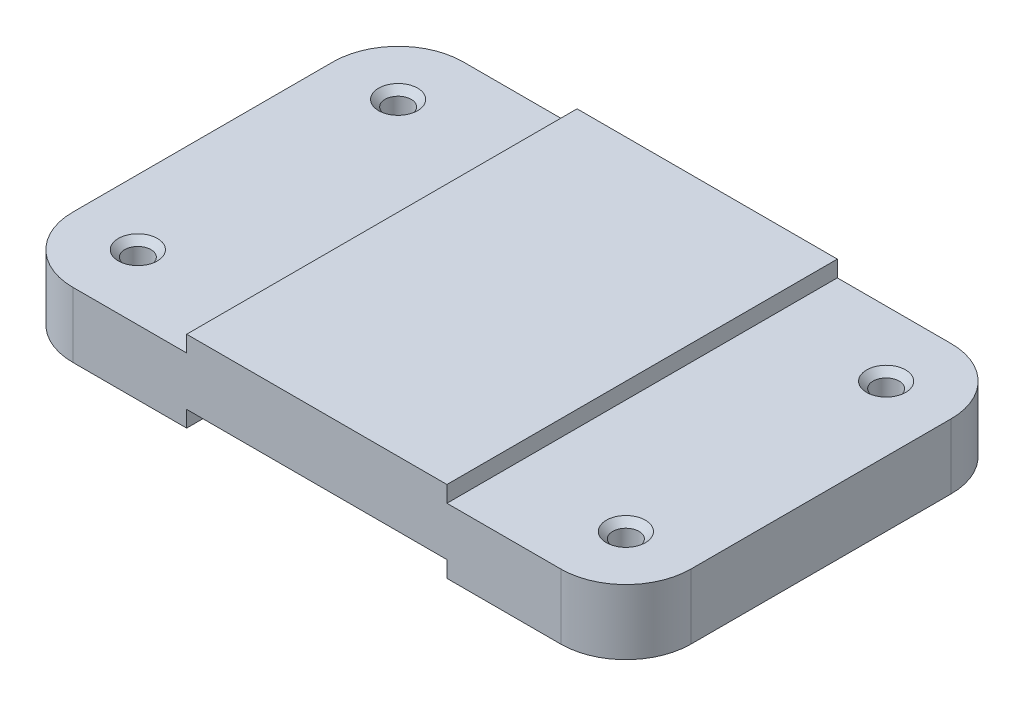
SolidWorks part; units mm, degrees
ref_plane "Front Plane" through (0, 0, 0) normal (0, 0, 1) x (1, 0, 0)
ref_plane "Top Plane" through (0, 0, 0) normal (0, 1, 0) x (1, 0, 0)
ref_plane "Right Plane" through (0, 0, 0) normal (1, 0, 0) x (0, 0, -1)
sketch "Sketch1" plane through (0, 0, 0) normal (0, 0, 1) x (1, 0, 0)
  line L0 (-25.4, 0) -> (25.4, 0)
  line L1 (-25.4, 0) -> (-25.4, -3.175)
  line L2 (-25.4, -3.175) -> (-60.325, -3.175)
  line L3 (-60.325, -3.175) -> (-60.325, -15.875)
  line L4 (-60.325, -15.875) -> (-25.4, -15.875)
  line L5 (-25.4, -15.875) -> (-25.4, -12.7)
  line L6 (-25.4, -12.7) -> (25.4, -12.7)
  line L7 (25.4, -12.7) -> (25.4, -15.875)
  line L8 (25.4, -15.875) -> (60.325, -15.875)
  line L9 (60.325, -15.875) -> (60.325, -3.175)
  line L10 (60.325, -3.175) -> (25.4, -3.175)
  line L11 (25.4, -3.175) -> (25.4, 0)
  line L12 (0, 52.0989) -> (0, -72.5728) construction
  point P15 (60.325, -9.525)
  point P16 (0, 0)
  dimension "D1" = 120.65
  dimension "D2" = 15.875
  dimension "D3" = 3.175
  dimension "D4" = 3.175
  dimension "D5" = 50.8
extrude "Boss-Extrude1" add sketch "Sketch1" along normal mid plane 76.2
fillet "Fillet1" radius 12.7 4 edges at (-60.325, -9.525, -38.1) (60.325, -9.525, -38.1) (-60.325, -9.525, 38.1) (60.325, -9.525, 38.1)
hole_wizard "1/4-20 Tapped Hole1" positions "Sketch2" profile "Sketch4" tap size "1/4-20" standard "ANSI Inch" end condition through all
sketch "Sketch2" plane through (0, -3.175, 0) normal (0, 1, 0) x (1, 0, 0)
  point P0 (-47.625, 25.4)
  point P3 (-47.625, -25.4)
  point P6 (47.625, -25.4)
  point P9 (47.625, 25.4)
sketch "Sketch4" plane through (-47.625, -3.175, -25.4) normal (1, 0, 0) x (0, 0, 1)
  line L0 (0, 0) -> (0, 12.7)
  line L1 (0, 12.7) -> (2.5527, 12.7)
  line L2 (2.5527, 12.7) -> (2.5527, 1.2573)
  line L3 (2.5527, 1.2573) -> (3.81, 0)
  line L5 (3.81, 0) -> (0, 0)
  line L6 (-2.5527, 1.2573) -> (-3.81, 0) construction
  line L11 (0, -6.35) -> (0, 107.95) construction
  dimension "Thru Tap Drill Dia." = 5.1054
  dimension "Thru Tap Drill Depth" = 12.7
  dimension "Near C'Sink Dia." = 7.62
  dimension "Near C'Sink Angle" = 90
cosmetic thread "Hole Thread1" parameters "D2"=6.35
cosmetic thread "Hole Thread2" parameters "D2"=6.35
cosmetic thread "Hole Thread3" parameters "D2"=6.35
cosmetic thread "Hole Thread4" parameters "D2"=6.35
